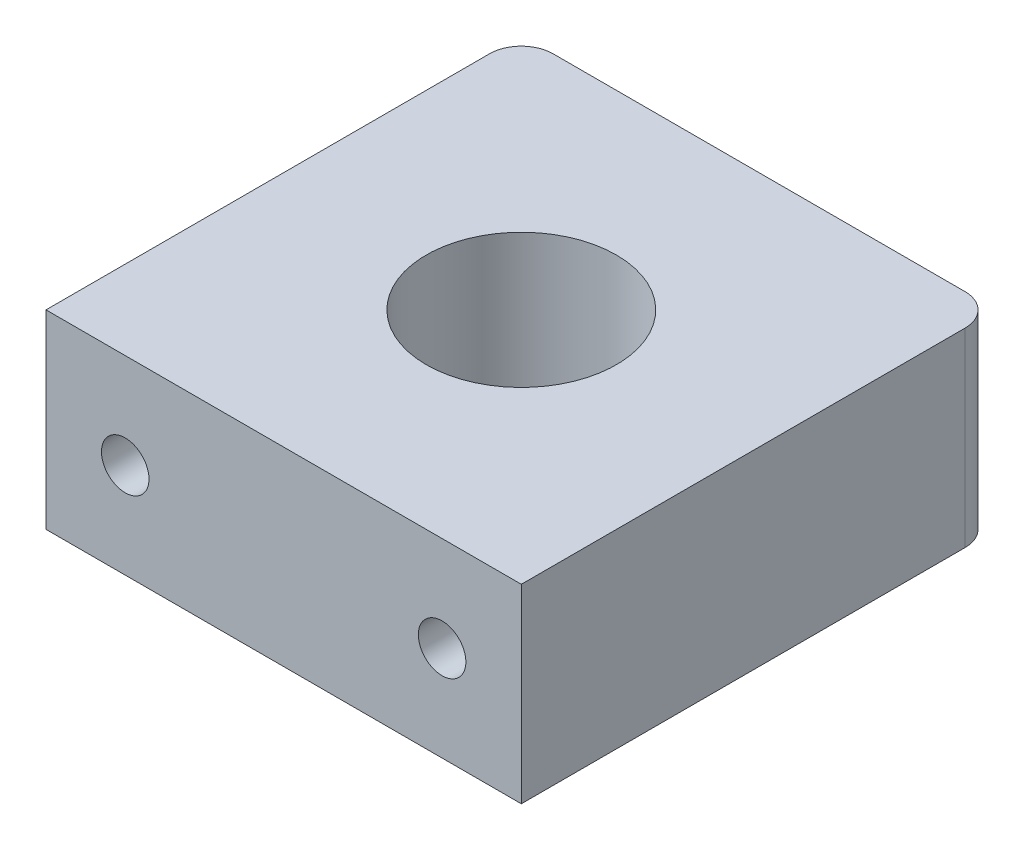
SolidWorks part; units mm, degrees
ref_plane "Front Plane" through (0, 0, 0) normal (0, 0, 1) x (1, 0, 0)
ref_plane "Top Plane" through (0, 0, 0) normal (0, 1, 0) x (1, 0, 0)
ref_plane "Right Plane" through (0, 0, 0) normal (1, 0, 0) x (0, 0, -1)
sketch "Sketch1" plane through (0, 0, 0) normal (0, 1, 0) x (1, 0, 0)
  line L0 (15, 0) -> (15, 30) construction
  line L1 (0, 0) -> (30, 0)
  line L2 (0, 0) -> (0, 30)
  line L3 (0, 30) -> (30, 30)
  line L4 (30, 0) -> (30, 30)
  line L5 (0, 15) -> (30, 15) construction
  circle A0 centre (15, 15) radius 6
  point P11 (15, 15)
  dimension "D1" = 12
  dimension "D2" = 15
  dimension "D3" = 30
  dimension "D4" = 30
extrude "Boss-Extrude1" add sketch "Sketch1" along normal blind 12
fillet "Fillet1" radius 2 2 edges at (30, 6, -30) (0, 6, -30)
sketch "Sketch2" plane through (0, 0, 0) normal (0, 0, 1) x (1, 0, 0)
  line L0 (0, 6) -> (30, 6) construction
  line L1 (0, 12) -> (0, 0) construction
  line L2 (30, 12) -> (30, 0) construction
  line L3 (15, 12) -> (15, 0) construction
  line L4 (0, 12) -> (30, 12) construction
  line L5 (0, 0) -> (30, 0) construction
  circle A0 centre (5, 6) radius 1.5
  circle A1 centre (25, 6) radius 1.5
  dimension "D1" = 3
  dimension "D2" = 20
extrude "Cut-Extrude1" cut sketch "Sketch2" against normal blind 5
